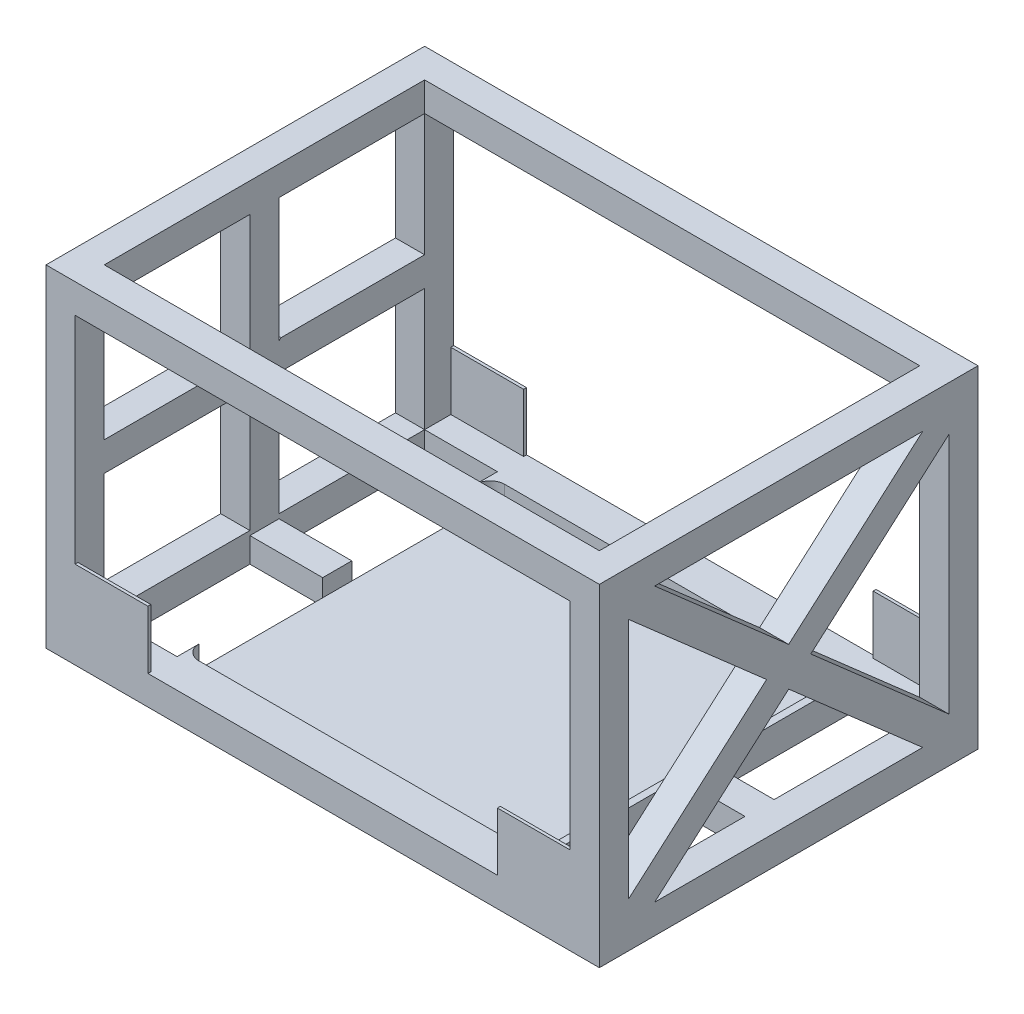
SolidWorks part; units mm, degrees
material "1060 Alloy"
ref_plane "Front Plane" through (0, 0, 0) normal (0, 0, 1) x (1, 0, 0)
ref_plane "Top Plane" through (0, 0, 0) normal (0, 1, 0) x (1, 0, 0)
ref_plane "Right Plane" through (0, 0, 0) normal (1, 0, 0) x (0, 0, -1)
ref_plane "Plane1" through (70, 0, 0) normal (-1, 0, 0) x (0, -1, 0)
sketch "Sketch1" plane through (70, 0, 0) normal (-1, 0, 0) x (0, -1, 0)
  line L0 (94, 130) -> (94, -130)
  line L1 (94, -130) -> (114, -130)
  line L2 (114, -130) -> (114, 130)
  line L3 (114, 130) -> (94, 130)
extrude "Boss-Extrude1" add sketch "Sketch1" against normal blind 10
sketch "Sketch2" plane through (0, -94, 0) normal (0, 1, 0) x (-1, 0, 0)
  line L0 (-80, 105) -> (-80, -105)
  line L1 (-70, -95) -> (-70, 95)
  arc A0 (-80, -105) -> (-70, -95) centre (-80, -95) ccw
  arc A1 (-70, 95) -> (-80, 105) centre (-80, 95) ccw
extrude "Cut-Extrude1" cut sketch "Sketch2" against normal blind 15
sketch "Sketch3" plane through (0, -94, 0) normal (0, 1, 0) x (-1, 0, 0)
  line L0 (-80, -110) -> (-70, -110)
  line L1 (-70, -110) -> (-70, -130)
  line L2 (-70, -130) -> (-80, -130)
  line L3 (-80, -130) -> (-80, -110)
extrude "Boss-Extrude2" add sketch "Sketch3" along normal blind 40
sketch "Sketch4" plane through (80, 0, 0) normal (1, 0, 0) x (0, 0, -1)
  line L0 (-130, -114) -> (-130, -94)
  line L1 (-130, -94) -> (110, -94)
  line L2 (110, -94) -> (110, -54)
  line L3 (110, -54) -> (130, -54)
  line L4 (130, -54) -> (130, -114)
  line L5 (130, -114) -> (-130, -114)
extrude "Boss-Extrude3" add sketch "Sketch4" along normal blind 230
sketch "Sketch5" plane through (310, 0, 0) normal (1, 0, 0) x (0, 0, -1)
  line L0 (110, -94) -> (110, -54)
  line L1 (110, -54) -> (130, -54)
  line L2 (130, -54) -> (130, -114)
  line L3 (130, -114) -> (-130, -114)
  line L4 (-130, -114) -> (-130, -54)
  line L5 (-130, -54) -> (-110, -54)
  line L6 (-110, -54) -> (-110, -94)
  line L7 (-110, -94) -> (110, -94)
extrude "Boss-Extrude4" add sketch "Sketch5" along normal blind 50
sketch "Sketch6" plane through (360, 0, 0) normal (1, 0, 0) x (0, 0, -1)
  line L0 (-130, 114) -> (130, 114)
  line L1 (130, 114) -> (130, -114)
  line L2 (130, -114) -> (-130, -114)
  line L3 (-130, -114) -> (-130, 114)
  line L4 (92.0259, -94) -> (0, -13.3004)
  line L5 (0, -13.3004) -> (-92.0259, -94)
  line L6 (-92.0259, -94) -> (92.0259, -94)
extrude "Boss-Extrude5" add sketch "Sketch6" along normal blind 20
sketch "Sketch7" plane through (70, 0, 0) normal (-1, 0, 0) x (0, 0, 1)
  line L0 (-10, -97) -> (10, -97)
  line L1 (10, -97) -> (10, -114)
  line L2 (10, -114) -> (-10, -114)
  line L3 (-10, -114) -> (-10, -97)
extrude "Boss-Extrude6" add sketch "Sketch7" along normal blind 50
sketch "Sketch8" plane through (70, 0, 0) normal (-1, 0, 0) x (0, 0, 1)
  line L0 (110, -114) -> (110, -54)
  line L1 (110, -54) -> (130, -54)
  line L2 (130, -54) -> (130, -114)
  line L3 (130, -114) -> (110, -114)
extrude "Boss-Extrude7" add sketch "Sketch8" along normal blind 50
sketch "Sketch9" plane through (70, 0, 0) normal (-1, 0, 0) x (0, 0, 1)
  line L0 (-110, -54) -> (-110, -114)
  line L1 (-110, -114) -> (-130, -114)
  line L2 (-130, -114) -> (-130, -54)
  line L3 (-130, -54) -> (-110, -54)
extrude "Boss-Extrude8" add sketch "Sketch9" along normal blind 50
sketch "Sketch10" plane through (360, 0, 0) normal (-1, 0, 0) x (0, 0, 1)
  line L0 (-110, 114) -> (-110, 94)
  line L1 (-110, 94) -> (-130, 94)
  line L2 (-130, 94) -> (-130, 114)
  line L3 (-130, 114) -> (-110, 114)
extrude "Boss-Extrude9" add sketch "Sketch10" along normal blind 340
sketch "Sketch11" plane through (360, 0, 0) normal (-1, 0, 0) x (0, 0, 1)
  line L0 (110, 94) -> (110, 114)
  line L1 (110, 114) -> (130, 114)
  line L2 (130, 114) -> (130, 94)
  line L3 (130, 94) -> (110, 94)
extrude "Boss-Extrude10" add sketch "Sketch11" along normal blind 340
ref_plane "Plane2" through (20, 0, 0) normal (1, 0, 0) x (0, 0, -1)
sketch "Sketch12" plane through (20, 0, 0) normal (1, 0, 0) x (0, 0, -1)
  line L0 (10, 8.7692) -> (10, 10)
  line L1 (10, 10) -> (11.4035, 10)
  line L2 (11.4035, 10) -> (10, 8.7692)
  line L3 (130, -114) -> (130, 114)
  line L4 (130, 114) -> (-130, 114)
  line L5 (-130, 114) -> (-130, -114)
  line L6 (-130, -114) -> (130, -114)
  line L7 (-10, -94) -> (-110, -94)
  line L8 (-110, -94) -> (-110, -10)
  line L9 (-110, -10) -> (-11.4035, -10)
  line L10 (-11.4035, -10) -> (-10, -8.7692)
  line L11 (-10, -8.7692) -> (-10, -94)
extrude "Boss-Extrude11" add sketch "Sketch12" against normal blind 20
sketch "Sketch13" plane through (70, 0, 0) normal (-1, 0, 0) x (0, -1, 0)
  line L0 (54, -130) -> (94, -130)
  line L1 (94, -130) -> (94, -110)
  line L2 (94, -110) -> (54, -110)
  line L3 (54, -110) -> (54, -130)
extrude "Cut-Extrude2" cut sketch "Sketch13" against normal blind 240
sketch "Sketch14" plane through (80, 0, 0) normal (-1, 0, 0) x (0, 0, 1)
  line L0 (-105, -109) -> (105, -109)
  line L1 (105, -109) -> (105, -94)
  line L2 (105, -94) -> (-105, -94)
  line L3 (-105, -94) -> (-105, -109)
extrude "Cut-Extrude3" cut sketch "Sketch14" against normal blind 230
ref_plane "Plane3" through (360, 0, 0) normal (1, 0, 0) x (0, 0, -1)
sketch "Sketch15" plane through (360, 0, 0) normal (1, 0, 0) x (0, 0, -1)
  line L0 (10, -94) -> (10, -114)
  line L1 (10, -114) -> (110, -114)
  line L2 (110, -114) -> (110, -94)
  line L3 (110, -94) -> (10, -94)
extrude "Cut-Extrude4" cut sketch "Sketch15" against normal blind 45
ref_plane "Plane4" through (0, 10, 0) normal (0, -1, 0) x (1, 0, 0)
sketch "Sketch16" plane through (0, 10, 0) normal (0, -1, 0) x (1, 0, 0)
  line L0 (0, 110) -> (0, 10)
  line L1 (0, 10) -> (20, 10)
  line L2 (20, 10) -> (20, 110)
  line L3 (20, 110) -> (0, 110)
extrude "Cut-Extrude5" cut sketch "Sketch16" against normal blind 84
sketch "Sketch17" plane through (0, 10, 0) normal (0, -1, 0) x (1, 0, 0)
  line L0 (20, -110) -> (20, -10)
  line L1 (20, -10) -> (0, -10)
  line L2 (0, -10) -> (0, -110)
  line L3 (0, -110) -> (20, -110)
extrude "Cut-Extrude6" cut sketch "Sketch17" against normal blind 84
ref_plane "Plane5" through (0, 0, -110) normal (0, 0, -1) x (-1, 0, 0)
sketch "Sketch18" plane through (0, 0, -110) normal (0, 0, -1) x (-1, 0, 0)
  line L0 (-20, -94) -> (0, -94)
  line L1 (0, -94) -> (0, -10)
  line L2 (0, -10) -> (-20, -10)
  line L3 (-20, -10) -> (-20, -94)
extrude "Cut-Extrude7" cut sketch "Sketch18" against normal blind 100
sketch "Sketch19" plane through (360, 0, 0) normal (1, 0, 0) x (0, 0, -1)
  line L0 (-10, -114) -> (-10, -94)
  line L1 (-10, -94) -> (-110, -94)
  line L2 (-110, -94) -> (-110, -114)
  line L3 (-110, -114) -> (-10, -114)
extrude "Cut-Extrude8" cut sketch "Sketch19" against normal blind 45
ref_plane "Plane6" through (0, 0, -128) normal (0, 0, -1) x (-1, 0, 0)
sketch "Sketch20" plane through (0, 0, -128) normal (0, 0, -1) x (-1, 0, 0)
  line L0 (-20, -54) -> (-70, -54)
  line L1 (-70, -54) -> (-70, -94)
  line L2 (-70, -94) -> (-20, -94)
  line L3 (-20, -94) -> (-20, -54)
extrude "Cut-Extrude9" cut sketch "Sketch20" against normal up to next
sketch "Sketch21" plane through (0, 0, -110) normal (0, 0, 1) x (1, 0, 0)
  line L0 (360, -54) -> (310, -54)
  line L1 (310, -54) -> (310, -94)
  line L2 (310, -94) -> (360, -94)
  line L3 (360, -94) -> (360, -54)
extrude "Cut-Extrude10" cut sketch "Sketch21" against normal blind 18
ref_plane "Plane7" through (0, 0, 128) normal (0, 0, 1) x (1, 0, 0)
sketch "Sketch22" plane through (0, 0, 128) normal (0, 0, 1) x (1, 0, 0)
  line L0 (20, -94) -> (70, -94)
  line L1 (70, -94) -> (70, -54)
  line L2 (70, -54) -> (20, -54)
  line L3 (20, -54) -> (20, -94)
extrude "Cut-Extrude11" cut sketch "Sketch22" against normal up to next
sketch "Sketch23" plane through (0, 0, 110) normal (0, 0, -1) x (-1, 0, 0)
  line L0 (-360, -54) -> (-360, -94)
  line L1 (-360, -94) -> (-310, -94)
  line L2 (-310, -94) -> (-310, -54)
  line L3 (-310, -54) -> (-360, -54)
extrude "Cut-Extrude12" cut sketch "Sketch23" against normal blind 18
sketch "Sketch24" plane through (360, 0, 0) normal (-1, 0, 0) x (0, 0, 1)
  line L0 (-92.0259, 94) -> (0, 13.3004)
  line L1 (0, 13.3004) -> (92.0259, 94)
  line L2 (92.0259, 94) -> (-92.0259, 94)
extrude "Cut-Extrude13" cut sketch "Sketch24" against normal through all
sketch "Sketch25" plane through (360, 0, 0) normal (-1, 0, 0) x (0, 0, 1)
  line L0 (110, 83.1612) -> (15.1671, 0)
  line L1 (15.1671, 0) -> (110, -83.1612)
  line L2 (110, -83.1612) -> (110, 83.1612)
extrude "Cut-Extrude14" cut sketch "Sketch25" against normal through all
sketch "Sketch26" plane through (380, 0, 0) normal (1, 0, 0) x (0, 0, -1)
  line L0 (15.1671, 0) -> (110, -83.1612)
  line L1 (110, -83.1612) -> (110, 83.1612)
  line L2 (110, 83.1612) -> (15.1671, 0)
extrude "Cut-Extrude15" cut sketch "Sketch26" against normal up to next
fillet "Fillet1" radius 10 2 edges at (310, -101.5, -105) (310, -101.5, 105)
